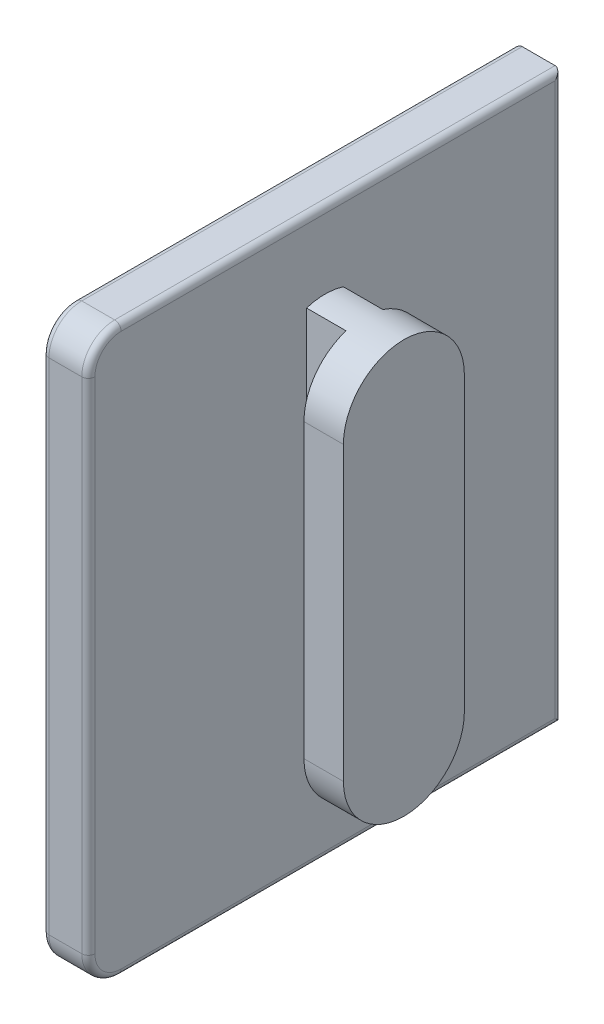
SolidWorks part; units mm, degrees
material "ABS_Black"
ref_plane "Přední rovina" through (0, 0, 0) normal (0, 0, 1) x (1, 0, 0)
ref_plane "Horní rovina" through (0, 0, 0) normal (0, 1, 0) x (1, 0, 0)
ref_plane "Pravá rovina" through (0, 0, 0) normal (1, 0, 0) x (0, 0, -1)
sketch "Skica1" plane through (0, 0, 0) normal (1, 0, 0) x (0, 0, -1)
  line L1 (-18, 21.5) -> (18, 21.5)
  line L2 (-18, 21.5) -> (-18, -21.5)
  line L3 (-18, -21.5) -> (18, -21.5)
  line L4 (18, 21.5) -> (18, -21.5)
  line L5 (-18, 21.5) -> (18, -21.5) construction
  line L6 (-18, -21.5) -> (18, 21.5) construction
  point P0 (0, 0)
  dimension "D1" = 36
  dimension "D2" = 43
extrude "Přidat vysunutím1" add sketch "Skica1" along normal blind 3.5
sketch "Skica2" plane through (3.5, 0, 0) normal (1, 0, 0) x (0, 0, -1)
  line L0 (0, 21.5) -> (0, -21.5) construction
  line L1 (18, 21.5) -> (-18, 21.5) construction
  line L2 (-18, -21.5) -> (18, -21.5) construction
  line L3 (-18, 0) -> (18, 0) construction
  line L4 (-18, 21.5) -> (-18, -21.5) construction
  line L5 (18, -21.5) -> (18, 21.5) construction
  line L8 (-1.4, 15.4818) -> (-1.4, -15.4818)
  line L10 (1.4, 15.4818) -> (1.4, -15.4818)
  arc A1 (-1.4, -15.4818) -> (1.4, -15.4818) centre (0, -11.1) ccw
  arc A2 (1.4, 15.4818) -> (-1.4, 15.4818) centre (0, 11.1) ccw
  point P12 (0, 0)
  dimension "D1" = 22.2
  dimension "D3" = 4.6
  dimension "D5" = 4.6
  dimension "D2" = 11.1
  dimension "D4" = 2.8
extrude "Přidat vysunutím2" add sketch "Skica2" along normal blind 3
sketch "Skica3" plane through (6.5, 0, 0) normal (1, 0, 0) x (0, 0, -1)
  line L0 (-4.6, -11.1) -> (-4.6, 11.1)
  line L1 (4.6, 11.1) -> (4.6, -11.1)
  arc A0 (4.6, 11.1) -> (-4.6, 11.1) centre (0, 11.1) ccw
  arc A1 (-4.6, -11.1) -> (4.6, -11.1) centre (0, -11.1) ccw
  dimension "D1" = 4.6
extrude "Přidat vysunutím3" add sketch "Skica3" along normal blind 3
fillet "Zaoblit1" radius 2.5 2 edges at (1.75, -21.5, 18) (1.75, 21.5, 18)
fillet "Zaoblit2" radius 0.5 12 edges at (3.5, -21.5, -1.25) (3.5, -20.7678, 17.2678) (3.5, 0, 18) (3.5, 20.7678, 17.2678) (0, 0, -18) (0, 21.5, -1.25) (0, 20.7678, 17.2678) (0, 0, 18) (0, -20.7678, 17.2678) (0, -21.5, -1.25) (3.5, 0, -18) (3.5, 21.5, -1.25)
